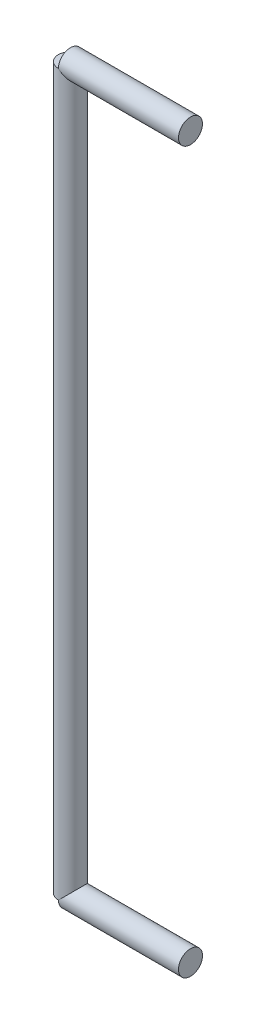
SolidWorks part; units mm, degrees
ref_plane "Front Plane" through (0, 0, 0) normal (0, 0, 1) x (1, 0, 0)
ref_plane "Top Plane" through (0, 0, 0) normal (0, 1, 0) x (1, 0, 0)
ref_plane "Right Plane" through (0, 0, 0) normal (1, 0, 0) x (0, 0, -1)
sketch "Sketch1" plane through (0, 0, 0) normal (0, 1, 0) x (1, 0, 0)
  circle A0 centre (0, 0) radius 0.5
  dimension "D1" = 1
extrude "Boss-Extrude2" add sketch "Sketch1" along normal blind 30
sketch "Sketch9" plane through (0, 0, 0) normal (1, 0, 0) x (0, 0, -1)
  line L0 (0.5, 30) -> (-0.5, 30) construction
  line L1 (-0.5, 0) -> (0.5, 0) construction
  circle A0 centre (0, 0) radius 0.5
  circle A1 centre (0, 30) radius 0.5
  dimension "D1" = 1
  dimension "D2" = 1
extrude "Boss-Extrude3" add sketch "Sketch9" along normal blind 5
